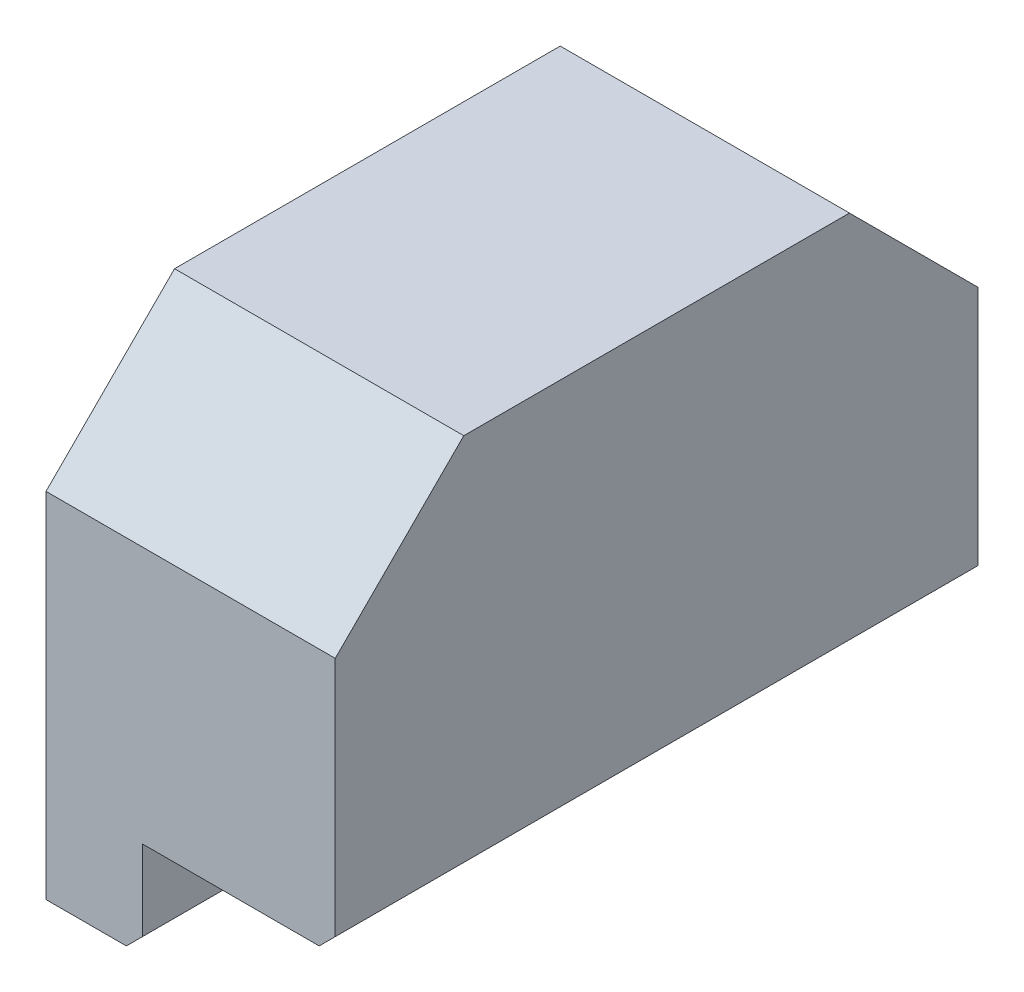
SolidWorks part; units mm, degrees
material "6061 合金"
ref_plane "前视基准面" through (0, 0, 0) normal (0, 0, 1) x (1, 0, 0)
ref_plane "上视基准面" through (0, 0, 0) normal (0, 1, 0) x (1, 0, 0)
ref_plane "右视基准面" through (0, 0, 0) normal (1, 0, 0) x (0, 0, -1)
sketch "草图1" plane through (0, 0, 0) normal (0, 0, 1) x (1, 0, 0)
  line L0 (0, 3) -> (0, 0)
  line L1 (0, 3) -> (6, 3)
  line L2 (6, 3) -> (6, 15)
  line L3 (6, 15) -> (-3, 15)
  line L4 (-3, 15) -> (-3, 0)
  line L5 (0, 0) -> (-3, 0)
  dimension "D1" = 3
  dimension "D2" = 3
  dimension "D3" = 6
  dimension "D4" = 12
extrude "凸台-拉伸1" add sketch "草图1" along normal blind 20
sketch "草图6" plane through (-3, 0, 0) normal (-1, 0, 0) x (0, 0, 1)
  line L1 (20, 0) -> (0, 0) construction
  circle A0 centre (10, 9) radius 5
  circle A1 centre (10, 9) radius 2
  point P9 (10, 0)
  dimension "D1" = 10
  dimension "D2" = 9
  dimension "D3" = 4
extrude "切除-拉伸2" cut sketch "草图6" against normal blind 2
chamfer "倒角2" distance 4 angle 45 2 edges at (1.5, 15, 20) (1.5, 15, 0)
chamfer "倒角3" distance 0.5 angle 45 4 edges at (6, 3, 10) (-3, 4, 10) (0, 0, 10) (-3, 7, 10)
hole_wizard "M3 螺纹孔1" positions "草图7" profile "草图8" tap size "M3" standard "GB"
sketch "草图7" plane through (0, 3, 0) normal (0, -1, 0) x (-1, 0, 0)
  line L0 (-5.5, -10) -> (0, -10) construction
  line L1 (-5.5, 0) -> (-5.5, -20) construction
  line L2 (0, -20) -> (0, 0) construction
  line L4 (0, -20) -> (0, 0) construction
  point P0 (-2.5, -5)
  point P2 (-2.5, -15)
  dimension "D1" = 10
  dimension "D2" = 2.5
sketch "草图8" plane through (2.5, 3, 5) normal (1, 0, 0) x (0, 0, -1)
  line L0 (0, 0) -> (0, 8.2511)
  line L1 (0, 8.2511) -> (1.25, 7.5)
  line L2 (1.25, 7.5) -> (1.25, 0)
  line L5 (1.25, 0) -> (0, 0)
  line L10 (0, 8.2511) -> (-1.25, 7.5) construction
  line L11 (0, -6.35) -> (0, 107.95) construction
  dimension "螺纹孔钻头直径" = 2.5
  dimension "螺纹孔钻头深度" = 7.5
  dimension "导头角度" = 118
cosmetic thread "孔螺蚊线1" parameters "D1"=6, "D2"=3
cosmetic thread "孔螺蚊线2" parameters "D1"=6, "D2"=3
